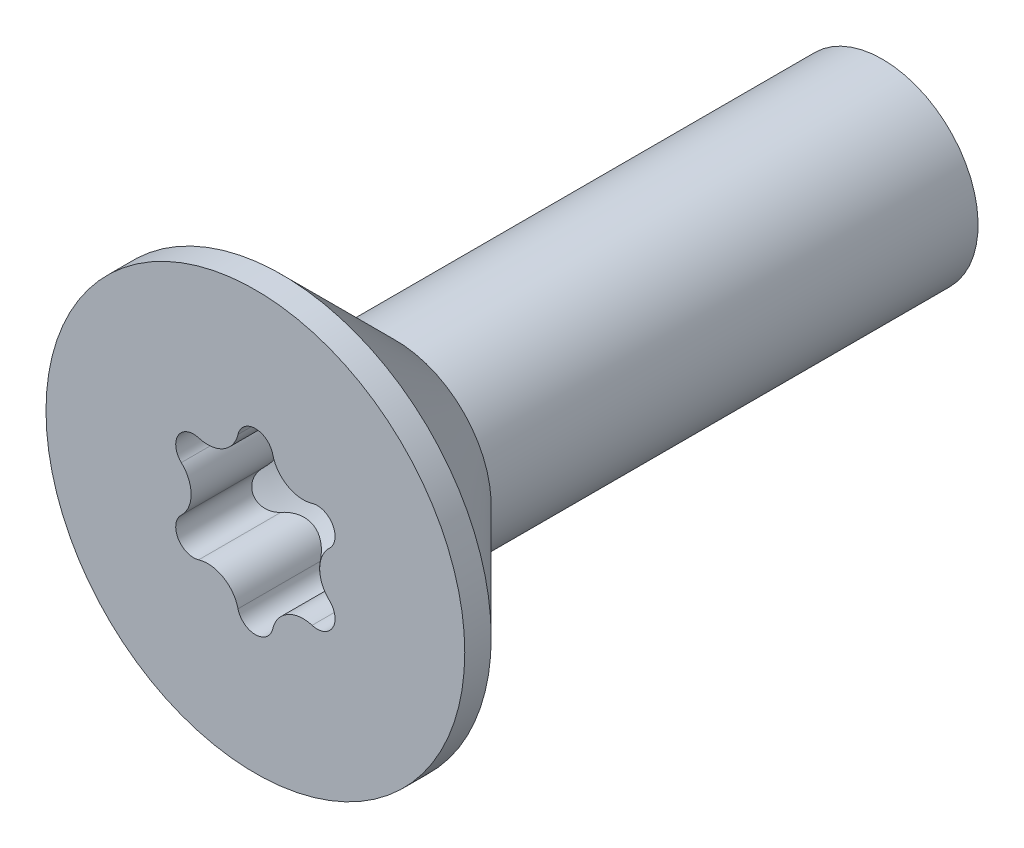
SolidWorks part; units mm, degrees
ref_plane "Front Plane" through (0, 0, 0) normal (0, 0, 1) x (1, 0, 0)
ref_plane "Top Plane" through (0, 0, 0) normal (0, 1, 0) x (1, 0, 0)
ref_plane "Right Plane" through (0, 0, 0) normal (1, 0, 0) x (0, 0, -1)
other "Configuration Table"
sketch "BodySke" plane through (0, 0, 0) normal (1, 0, 0) x (0, 0, -1)
  line L0 (0, 0) -> (-1787.2758, 0) construction
  line L1 (0, 0) -> (0, 3.285)
  line L2 (0.415, 3.285) -> (2.2, 1.5)
  line L3 (0.415, -3.285) -> (2.2, -1.5) construction
  line L4 (2.2, 1.5) -> (10, 1.5)
  line L5 (10, 1.5) -> (10, 0)
  line L6 (10, 0) -> (0, 0)
  line L7 (0, 0) -> (0, 50000) construction
  line L8 (0.415, 3.285) -> (0, 3.285)
  dimension "D" = 3
  dimension "Dk" = 6.57
  dimension "K" = 2.2
  dimension "L" = 10
  dimension "D1" = 90
  dimension "B" = 10
revolve "Base-Revolve" add sketch "BodySke" angle 360 about L0
cosmetic thread "ThreadCosmetic" [suppressed] parameters "ThdLen"=7.8, "MinorDia"=2.439
sketch "PreBSke" plane through (0, 0, 0) normal (1, 0, 0) x (0, 0, -1)
  line L0 (0, 0) -> (-50000, 0) construction
  line L1 (0, 0) -> (0, 1.4)
  line L2 (0, 3.7) -> (0, -3.7) construction
  line L3 (0, 1.4) -> (1.18, 1.4)
  line L4 (1.18, 1.4) -> (2.0212, 0)
  line L5 (2.0212, 0) -> (0, 0)
  line L6 (1.18, -1.4) -> (2.0212, 0) construction
  dimension "T" = 1.18
  dimension "A" = 2.8
  dimension "D1" = 118
revolve "PreBroach" cut sketch "PreBSke" angle 360 about L0
sketch "HexSke" plane through (0, 0, 0) normal (0, 0, 1) x (1, 0, 0)
  line L0 (0, 0) -> (-43301.2702, 25000) construction
  line L1 (0, 0) -> (-43301.2702, -25000) construction
  line L2 (0, 0) -> (50000, 0) construction
  arc A0 (-1.1621, -0.3564) -> (-1.1621, 0.3564) centre (-1.4984, 0) ccw
  arc A1 (-1.2124, 0.7) -> (-1.1621, 0.3564) centre (-0.9699, 0.56) ccw
  arc A2 (-1.1621, -0.3564) -> (-1.2124, -0.7) centre (-0.9699, -0.56) ccw
  arc A3 (-0.8897, 0.8282) -> (-1.2124, 0.7) centre (-0.9699, 0.56) ccw
  circle A4 centre (0, 0) radius 1.0084 construction
  circle A5 centre (0, 0) radius 1.4 construction
  arc A6 (-0.8897, 0.8282) -> (-0.2724, 1.1846) centre (-0.7492, 1.2977) ccw
  arc A7 (0, 1.4) -> (-0.2724, 1.1846) centre (0, 1.12) ccw
  arc A8 (0.2724, 1.1846) -> (0, 1.4) centre (0, 1.12) ccw
  arc A9 (0.2724, 1.1846) -> (0.8897, 0.8282) centre (0.7492, 1.2977) ccw
  arc A10 (1.2124, 0.7) -> (0.8897, 0.8282) centre (0.9699, 0.56) ccw
  arc A11 (1.1621, 0.3564) -> (1.2124, 0.7) centre (0.9699, 0.56) ccw
  arc A12 (1.1621, 0.3564) -> (1.1621, -0.3564) centre (1.4984, 0) ccw
  arc A13 (1.2124, -0.7) -> (1.1621, -0.3564) centre (0.9699, -0.56) ccw
  arc A14 (0.8897, -0.8282) -> (1.2124, -0.7) centre (0.9699, -0.56) ccw
  arc A15 (0.8897, -0.8282) -> (0.2724, -1.1846) centre (0.7492, -1.2977) ccw
  arc A16 (0, -1.4) -> (0.2724, -1.1846) centre (0, -1.12) ccw
  arc A17 (-0.2724, -1.1846) -> (0, -1.4) centre (0, -1.12) ccw
  arc A18 (-0.2724, -1.1846) -> (-0.8897, -0.8282) centre (-0.7492, -1.2977) ccw
  arc A19 (-1.2124, -0.7) -> (-0.8897, -0.8282) centre (-0.9699, -0.56) ccw
  circle A20 centre (0, 0) radius 1.4 construction
  circle A21 centre (0, 0) radius 1.4
  point P56 (0, 0)
  circle M6 centre (0, 0) radius 1.4
  dimension "B" = 2.0169
  dimension "Ri" = 0.28
  dimension "Re" = 0.49
  dimension "D1" = 60
  dimension "D5" = 6
extrude "Hexalobular" add sketch "HexSke" against normal up to next contours A2 A0 A1 M6 | A7 A3 A6 M6 | A10 A8 A9 M6 | A13 A11 A12 M6 | A16 A14 A15 M6 | A19 A17 A18 M6
sketch "ThdSchSke" plane through (0, 0, 0) normal (1, 0, 0) x (0, 0, -1)
  line L0 (10.1619, 1.5) -> (10, 1.2195)
  line L1 (10, 1.2195) -> (9.8381, 1.5)
  line L2 (9.8381, 1.5) -> (10.1619, 1.5)
  line L3 (10, 1.2195) -> (10, 1.5) construction
  line L4 (10, -1.5) -> (10, 1.5) construction
  line L5 (10, 1.5) -> (2.2, 1.5) construction
  line L6 (0, 0) -> (-50000, 0) construction
  dimension "MinorDia" = 2.439
  dimension "D1" = 60
  dimension "D2" = 0.3239
revolve "ThreadSchematic" cut sketch "ThdSchSke" angle 360 about L6
ref_plane "ThreadPlane" through (0, 0, -2.2) normal (0, 0, -1) x (-1, 0, 0)
pattern_linear "ThdSchPat" [suppressed] count 13
equation "\"MinorDia@ThreadCosmetic\" = \"MinorDia@ThdSchSke\""
equation "\"ThdLen@ThreadCosmetic\" = \"ThreadLength\""
equation "\"Ri@HexSke\"= .1 * \"A@PreBSke\""
equation "\"Re@HexSke\"= .175 * \"A@PreBSke\""
equation "\"ThreadLength\"= IIF ( \"B@BodySke\" = \"L@BodySke\" , \"L@BodySke\" - \"K@BodySke\" , \"B@BodySke\" )"
equation "\"ThdLen@ThreadPlane\"=\"ThreadLength\""
